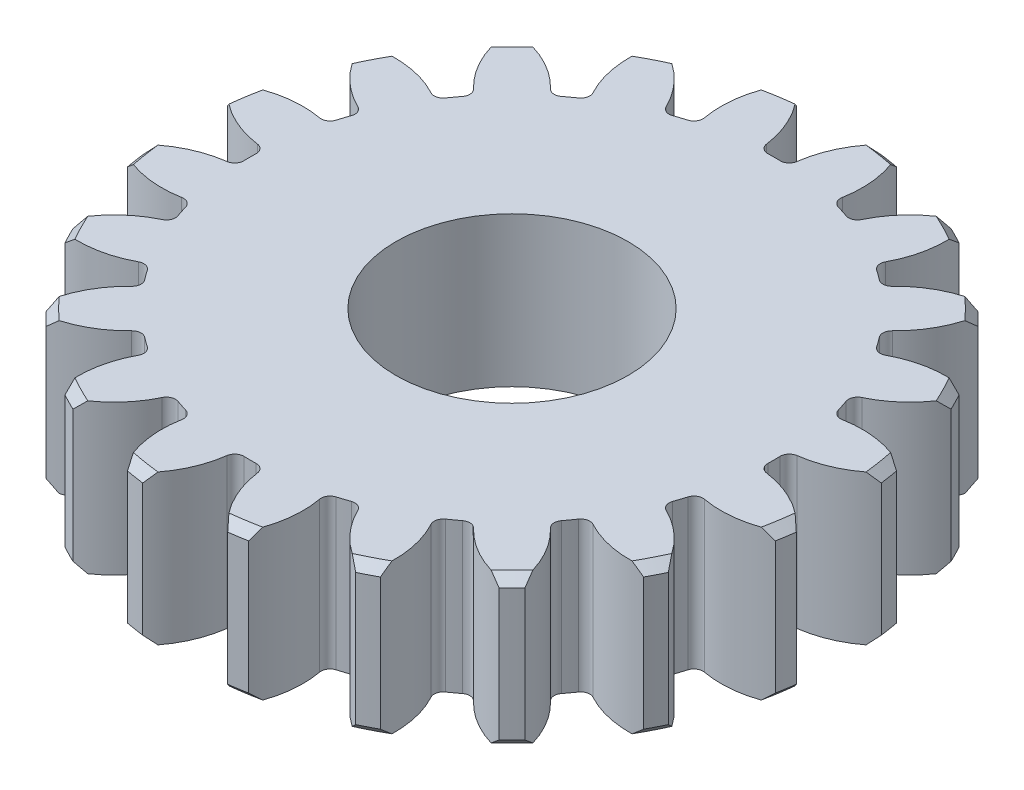
SolidWorks part; units mm, degrees
ref_plane "Front Plane" through (0, 0, 0) normal (0, 0, 1) x (1, 0, 0)
ref_plane "Top Plane" through (0, 0, 0) normal (0, 1, 0) x (1, 0, 0)
ref_plane "Right Plane" through (0, 0, 0) normal (1, 0, 0) x (0, 0, -1)
sketch "Sketch1" plane through (0, 0, 0) normal (0, 1, 0) x (1, 0, 0)
  circle A0 centre (0, 0) radius 20
  circle A1 centre (0, 0) radius 22
  circle A2 centre (0, 0) radius 17.5
  dimension "D1" = 40
  dimension "addendum" = 2
  dimension "dedendum" = 2.5
extrude "Boss-Extrude1" add sketch "Sketch1" along normal blind 10 contours A1
sketch "Sketch2" plane through (0, 0, 0) normal (0, -1, 0) x (1, 0, 0)
  line L0 (0, 0) -> (0, 41.9432) construction
  line L1 (-0.9626, 17.4735) -> (0, 0) construction
  line L2 (0.9626, 17.4735) -> (0, 0) construction
  line L3 (-1.5692, 19.9383) -> (1.5692, 19.9383) construction
  line L4 (-5.0152, 27.5) -> (-4.0305, 25.3393) construction
  line L5 (-1.5692, 19.9383) -> (4.5196, 22.7132) construction
  line L6 (-1.5692, 19.9383) -> (1.8919, 20.2107) construction
  line L7 (0, 0) -> (6.5686, 41.4726) construction
  line L8 (1.5692, 19.9383) -> (4.6689, 19.4474) construction
  arc A0 (-2.8367, 21.8164) -> (-0.9626, 17.4735) centre (-7.8048, 17.0966) cw
  circle A1 centre (0, 0) radius 22 construction
  circle A2 centre (0, 0) radius 17.5 construction
  arc A3 (2.8367, 21.8164) -> (0.9626, 17.4735) centre (7.8048, 17.0966) ccw
  circle A4 centre (0, 0) radius 20 construction
  arc A5 (0.9626, 17.4735) -> (-0.9626, 17.4735) centre (0, 0) ccw
  arc A6 (2.8367, 21.8164) -> (-2.8367, 21.8164) centre (0, 0) ccw
  point P13 (-1.5692, 19.9383)
  point P14 (1.5692, 19.9383)
  dimension "D1" = 20
  dimension "D2" = 9
extrude "Cut-Extrude1" cut sketch "Sketch2" against normal up to surface (10 mm away) up to face at (0, 10, 22)
fillet "Fillet1" radius 0.6 2 edges at (0.9626, 5, 17.4735) (-0.9626, 5, 17.4735)
chamfer "Chamfer1" distance 0.6 angle 45 2 edges at (0, 0, -22) (0, 10, -22)
pattern_circular "CirPattern1" count 20 over 360 about axis through (0, 0, 0) along (0, 1, 0) of "Cut-Extrude1", "Fillet1"
sketch "Sketch3" plane through (0, 0, 0) normal (0, -1, 0) x (1, 0, 0)
  circle A0 centre (0, 0) radius 7.75
  dimension "D1" = 15.5
extrude "Cut-Extrude2" cut sketch "Sketch3" against normal up to surface (10 mm away) up to face at (0, 10, 0)
sketch "Sketch4" plane through (0, 10, 0) normal (0, 1, 0) x (1, 0, 0)
  point P0 (0, 0)
equation "\"module\"= 2mm"
equation "\"noTeeth\"= 20"
equation "\"pressureAngle\"= 20deg"
equation "\"width\"= 10mm"
equation "\"D1@Sketch1\"=\"module\"*\"noTeeth\""
equation "\"dedendum@Sketch1\" = \"module\" * 1.25"
equation "\"addendum@Sketch1\" = \"module\""
equation "\"D1@Sketch2\"=\"pressureAngle\""
equation "\"D2@Sketch2\"=180/\"noTeeth\""
equation "\"D1@Fillet1\"=0.3*\"module\""
equation "\"D1@Chamfer1\"=0.3*\"module\""
equation "\"D1@CirPattern1\"=\"noTeeth\""
